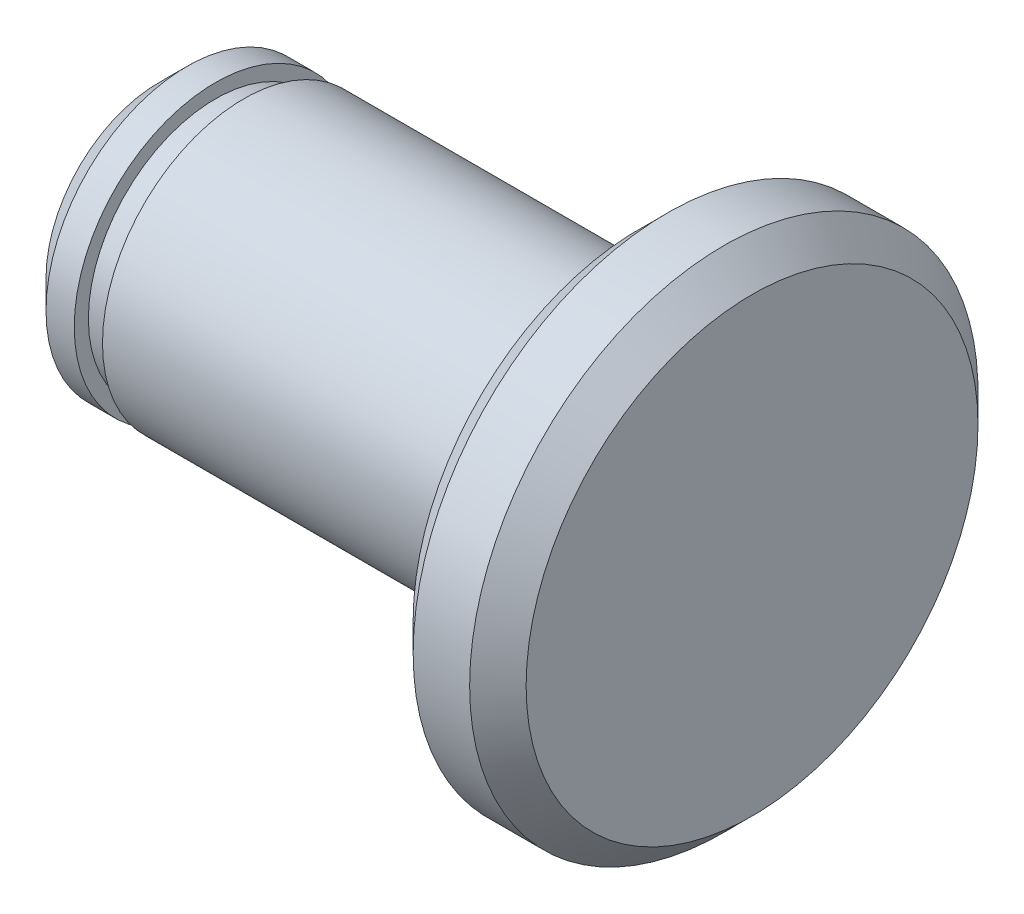
SolidWorks part; units mm, degrees
ref_plane "Front Plane" through (0, 0, 0) normal (1, 0, 0) x (0, 1, 0)
ref_plane "Top Plane" through (0, 0, 0) normal (0, 0, 1) x (0, 1, 0)
ref_plane "Right Plane" through (0, 0, 0) normal (0, 1, 0) x (-1, 0, 0)
sketch "Sketch1" plane through (0, 0, 0) normal (0, 1, 0) x (-1, 0, 0)
  line L0 (0, 0) -> (0, 9) construction
  line L1 (-1, 9) -> (-3, 9)
  line L2 (-4, 8) -> (-4, 0)
  line L3 (-4, 0) -> (17, 0) construction
  line L4 (17, 0) -> (17, 4)
  line L5 (16, 5) -> (15, 5)
  line L6 (0, 8) -> (0, 5)
  line L7 (15, 5) -> (15, 4.5)
  line L8 (15, 4.5) -> (14, 4.5)
  line L9 (14, 4.5) -> (14, 5)
  line L10 (14, 5) -> (0, 5)
  line L11 (17, 4) -> (16, 5)
  line L12 (-1, 9) -> (0, 8)
  line L13 (-3, 9) -> (-4, 8)
  line L14 (17, 0) -> (-4, 0)
  point P4 (-4, 9)
  point P7 (17, 5)
  dimension "D1" = 10
  dimension "D2" = 18
  dimension "D3" = 4
  dimension "D4" = 17
  dimension "D5" = 0.5
  dimension "D6" = 14
  dimension "D7" = 1
revolve "Revolve1" add sketch "Sketch1" angle 360 about L14
